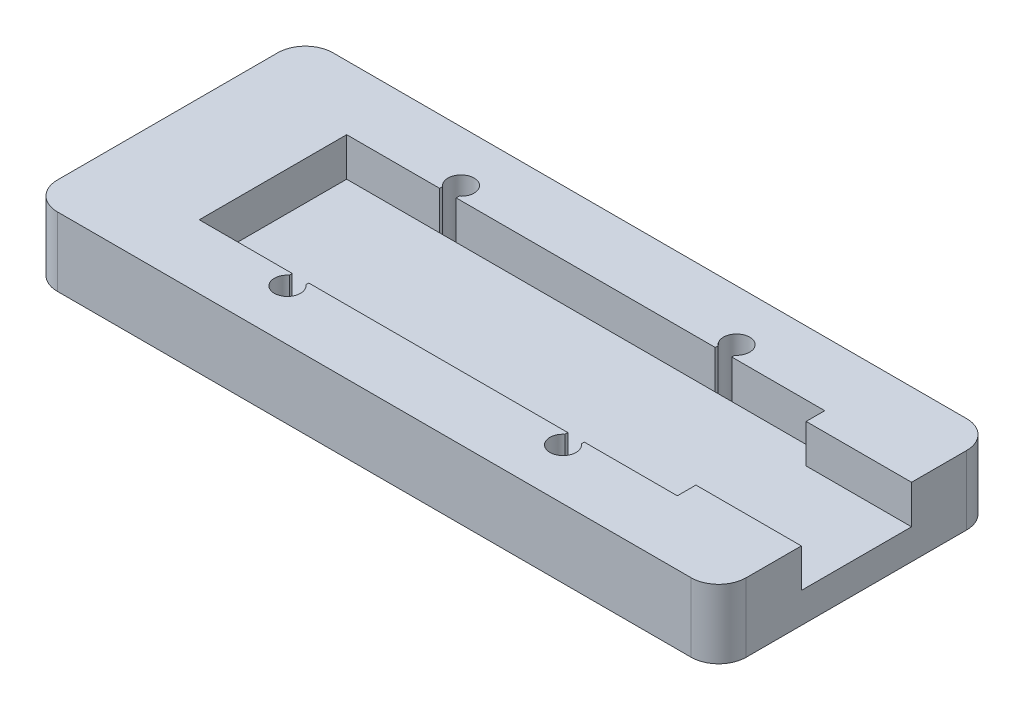
SolidWorks part; units mm, degrees
ref_plane "前基準面" through (0, 0, 0) normal (0, 0, 1) x (1, 0, 0)
ref_plane "上基準面" through (0, 0, 0) normal (0, 1, 0) x (1, 0, 0)
ref_plane "右基準面" through (0, 0, 0) normal (1, 0, 0) x (0, 0, -1)
sketch "草圖1" plane through (0, 0, 0) normal (0, 1, 0) x (1, 0, 0)
  line L1 (-23, -10) -> (23, -10)
  line L2 (-25, -8) -> (-25, 8)
  line L3 (-23, 10) -> (23, 10)
  line L4 (25, -8) -> (25, 8)
  line L5 (-25, -10) -> (25, 10) construction
  line L6 (-25, 10) -> (25, -10) construction
  arc A0 (23, 10) -> (25, 8) centre (23, 8) cw
  arc A1 (25, -8) -> (23, -10) centre (23, -8) cw
  arc A2 (-23, -10) -> (-25, -8) centre (-23, -8) cw
  arc A3 (-25, 8) -> (-23, 10) centre (-23, 8) cw
  point P0 (0, 0)
  dimension "D3" = 2
  dimension "D1" = 20
  dimension "D2" = 50
extrude "填料-伸長1" add sketch "草圖1" along normal blind 5
sketch "草圖2" plane through (0, 5, 0) normal (0, 1, 0) x (1, 0, 0)
  line L0 (25, -8) -> (25, 8) construction
  line L1 (-17.35, -5.35) -> (17.35, -5.35)
  line L2 (-17.35, -5.35) -> (-17.35, 5.35)
  line L3 (-17.35, 5.35) -> (17.35, 5.35)
  line L4 (17.35, -5.35) -> (17.35, -4)
  line L5 (-17.35, -5.35) -> (17.35, 5.35) construction
  line L6 (-17.35, 5.35) -> (17.35, -5.35) construction
  line L7 (17.35, -4) -> (25, -4)
  line L8 (0, 0) -> (-34.7994, 0) construction
  line L9 (17.35, 4) -> (25, 4)
  line L10 (25, -4) -> (25, 4)
  line L11 (17.35, 4) -> (17.35, 5.35)
  point P0 (0, 0)
  dimension "D1" = 34.7
  dimension "D2" = 10.7
  dimension "D3" = 8
extrude "除料-伸長1" cut sketch "草圖2" against normal blind 2.8
sketch "草圖3" plane through (0, 5, 0) normal (0, 1, 0) x (1, 0, 0)
  line L0 (0, 0) -> (0, 12.8997) construction
  line L3 (17.35, 5.35) -> (-17.35, 5.35) construction
  line L4 (-10.6, 5.5635) -> (-10.6, 5.35)
  line L5 (-9.4, 5.5635) -> (-9.4, 5.35)
  line L6 (-10, 6.3) -> (-10, 2.7692) construction
  line L7 (-10.6, 5.35) -> (-9.4, 5.35)
  line L9 (0, 0) -> (-19.1874, 0) construction
  line L10 (-10.6, -5.35) -> (-9.4, -5.35)
  line L11 (-10.6, -5.5635) -> (-10.6, -5.35)
  line L12 (-9.4, -5.5635) -> (-9.4, -5.35)
  line L13 (10.6, 5.5635) -> (10.6, 5.35)
  line L14 (9.4, 5.5635) -> (9.4, 5.35)
  line L15 (9.4, -5.5635) -> (9.4, -5.35)
  line L16 (10.6, -5.5635) -> (10.6, -5.35)
  line L17 (10.6, -5.35) -> (9.4, -5.35)
  line L18 (9.4, 5.35) -> (10.6, 5.35)
  arc A0 (-9.4, 5.5635) -> (-10.6, 5.5635) centre (-10, 6.3) ccw
  arc A1 (-9.4, -5.5635) -> (-10.6, -5.5635) centre (-10, -6.3) cw
  arc A2 (9.4, 5.5635) -> (10.6, 5.5635) centre (10, 6.3) cw
  arc A3 (9.4, -5.5635) -> (10.6, -5.5635) centre (10, -6.3) ccw
  dimension "D1" = 1.9
  dimension "D2" = 10
  dimension "D3" = 1.2
extrude "除料-伸長2" cut sketch "草圖3" against normal blind 5
